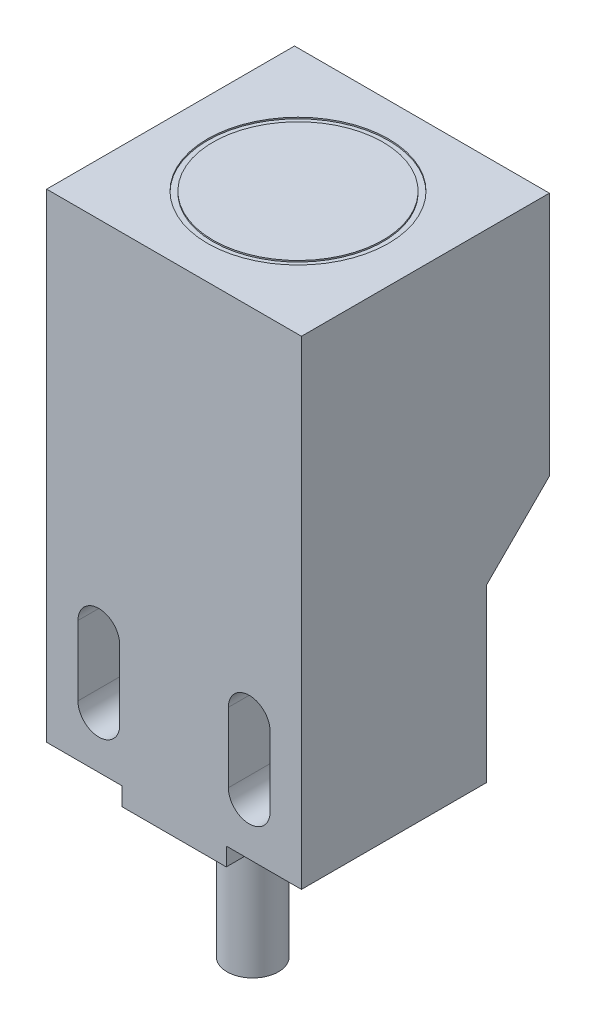
SolidWorks part; units mm, degrees
ref_plane "Plan de face" through (0, 0, 0) normal (0, 0, 1) x (1, 0, 0)
ref_plane "Plan de dessus" through (0, 0, 0) normal (0, 1, 0) x (1, 0, 0)
ref_plane "Plan de droite" through (0, 0, 0) normal (1, 0, 0) x (0, 0, -1)
sketch "Esquisse1" plane through (0, 0, 0) normal (0, 1, 0) x (1, 0, 0)
  line L1 (-9.15, 8.9) -> (9.15, 8.9)
  line L2 (-9.15, 8.9) -> (-9.15, -8.9)
  line L3 (-9.15, -8.9) -> (9.15, -8.9)
  line L4 (9.15, 8.9) -> (9.15, -8.9)
  point P4 (0, 8.9)
  point P6 (-9.15, 0)
  dimension "D1" = 18.3
  dimension "D2" = 17.8
extrude "Boss.-Extru.1" add sketch "Esquisse1" against normal blind 34.4
sketch "Esquisse2" plane through (0, 0, 0) normal (1, 0, 0) x (0, 0, -1)
  line L0 (8.9, -17.6) -> (4.4, -22.1)
  line L1 (8.9, -34.4) -> (8.9, 0) construction
  line L2 (4.4, -22.1) -> (4.4, -34.4)
  line L3 (-8.9, -34.4) -> (8.9, -34.4) construction
  line L4 (4.4, -34.4) -> (8.9, -34.4)
  line L5 (8.9, -34.4) -> (8.9, -17.6)
  dimension "D1" = 16.8
  dimension "D2" = 4.5
  dimension "D3" = 45
extrude "Enlèv. mat.-Extru.1" cut sketch "Esquisse2" against normal through all both and the other way through all
sketch "Esquisse3" plane through (0, 0, 0) normal (0, 0, 1) x (1, 0, 0)
  line L0 (5.4, -30.7) -> (5.4, -25.7) construction
  line L1 (3.9, -30.7) -> (3.9, -25.7)
  line L2 (6.9, -30.7) -> (6.9, -25.7)
  line L3 (0, -9.79) -> (0, 9.79) construction
  line L4 (-5.4, -30.7) -> (-5.4, -25.7) construction
  line L5 (-3.9, -30.7) -> (-3.9, -25.7)
  line L6 (-6.9, -30.7) -> (-6.9, -25.7)
  line L7 (-9.15, -34.4) -> (9.15, -34.4) construction
  arc A0 (3.9, -30.7) -> (6.9, -30.7) centre (5.4, -30.7) ccw
  arc A1 (6.9, -25.7) -> (3.9, -25.7) centre (5.4, -25.7) ccw
  arc A2 (-3.9, -30.7) -> (-6.9, -30.7) centre (-5.4, -30.7) cw
  arc A3 (-6.9, -25.7) -> (-3.9, -25.7) centre (-5.4, -25.7) cw
  point P2 (5.4, -28.2)
  point P11 (-5.4, -28.2)
  point P16 (3.9, -32.5431)
  point P17 (5.4, -32.2)
  point P18 (5.4, -24.2)
  dimension "D1" = 10.8
  dimension "D2" = 3
  dimension "D3" = 8
  dimension "D4" = 2.2
extrude "Enlèv. mat.-Extru.2" cut sketch "Esquisse3" against normal through all both and the other way through all
sketch "Esquisse4" plane through (0, 0, -4.4) normal (0, 0, -1) x (-1, 0, 0)
  line L1 (0, -17.6) -> (0, -22.1) construction
  line L2 (9.15, -17.6) -> (-9.15, -17.6) construction
  line L3 (9.15, -22.1) -> (-9.15, -22.1) construction
  circle A0 centre (0, -19.85) radius 4.25
  point P2 (0, -19.85)
  dimension "D1" = 8.5
extrude "Boss.-Extru.2" add sketch "Esquisse4" along normal blind 2.2
sketch "Esquisse5" plane through (0, 0, -6.6) normal (0, 0, -1) x (-1, 0, 0)
  circle A0 centre (0, -19.85) radius 2.45
  dimension "D1" = 4.9
extrude "Boss.-Extru.3" add sketch "Esquisse5" along normal blind 2.1
sketch "Esquisse6" plane through (0, -34.4, 0) normal (0, -1, 0) x (1, 0, 0)
  line L0 (0, 8.9) -> (0, 3.25) construction
  line L1 (-9.15, 8.9) -> (9.15, 8.9) construction
  line L2 (3.75, 8.9) -> (3.75, 3.25)
  line L3 (-3.75, 8.9) -> (-3.75, 3.25)
  line L6 (-3.75, 8.9) -> (3.75, 8.9)
  arc A2 (-3.75, 3.25) -> (3.75, 3.25) centre (0, 3.25) ccw
  point P5 (0, 5.575)
  point P10 (0, -0.5)
  point P14 (0, 0)
  point P15 (0, 0)
  point P16 (0, 0)
  dimension "D1" = 7.5
  dimension "D2" = 9.4
extrude "Boss.-Extru.4" add sketch "Esquisse6" along normal blind 1.3
sketch "Esquisse7" plane through (0, -35.7, 0) normal (0, -1, 0) x (1, 0, 0)
  circle A0 centre (0, 3.25) radius 1.85
  dimension "D1" = 3.7
extrude "Boss.-Extru.5" add sketch "Esquisse7" along normal blind 10.3
sketch "Esquisse8" plane through (0, 0, 0) normal (0, 1, 0) x (1, 0, 0)
  circle A0 centre (0, 0) radius 6.5
  circle A1 centre (0, 0) radius 6.1
  dimension "D1" = 13
  dimension "D2" = 0.4
extrude "Enlèv. mat.-Extru.3" cut sketch "Esquisse8" against normal blind 0.1
